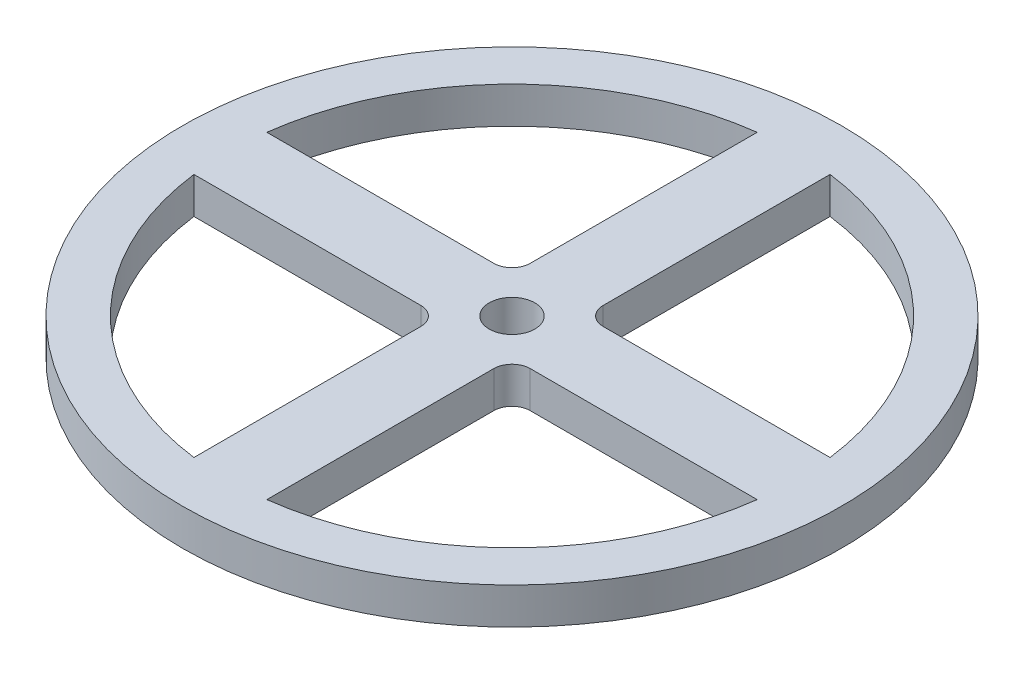
SolidWorks part; units mm, degrees
ref_plane "Front Plane" through (0, 0, 0) normal (0, 0, 1) x (1, 0, 0)
ref_plane "Top Plane" through (0, 0, 0) normal (0, 1, 0) x (1, 0, 0)
ref_plane "Right Plane" through (0, 0, 0) normal (1, 0, 0) x (0, 0, -1)
sketch "Sketch1" plane through (0, 0, 0) normal (0, 1, 0) x (1, 0, 0)
  line L0 (-43.2051, 0) -> (60.4147, 0) construction
  line L1 (0, 48.3176) -> (0, -50.4298) construction
  line L2 (-30.8921, -4) -> (-6, -4)
  line L3 (-4, 30.8921) -> (-4, 6)
  line L4 (-30.8921, 4) -> (-6, 4)
  line L5 (4, 30.8921) -> (4, 6)
  line L6 (-4, -6) -> (-4, -30.8921)
  line L7 (-4, 48.3176) -> (-4, -50.4298) construction
  line L8 (4, 48.3176) -> (4, -50.4298) construction
  line L9 (-43.2051, 4) -> (60.4147, 4) construction
  line L10 (-43.2051, -4) -> (60.4147, -4) construction
  line L11 (6, 4) -> (30.8921, 4)
  line L12 (6, -4) -> (30.8921, -4)
  line L13 (4, -6) -> (4, -30.8921)
  circle A0 centre (0, 0) radius 36.15
  circle A1 centre (0, 0) radius 2.5
  arc A2 (-30.8921, -4) -> (-4, -30.8921) centre (0, 0) ccw
  arc A5 (-6, -4) -> (-4, -6) centre (-6, -6) cw
  arc A6 (-6, 4) -> (-4, 6) centre (-6, 6) ccw
  arc A7 (4, 6) -> (6, 4) centre (6, 6) ccw
  arc A9 (6, -4) -> (4, -6) centre (6, -6) ccw
  arc A10 (-4, 30.8921) -> (-30.8921, 4) centre (0, 0) ccw
  circle A11 centre (0, 0) radius 31.15 construction
  arc A12 (30.8921, 4) -> (4, 30.8921) centre (0, 0) ccw
  arc A13 (4, -30.8921) -> (30.8921, -4) centre (0, 0) ccw
  point P38 (29.9323, 9.1512)
  dimension "D1" = 72.3
  dimension "D2" = 5
  dimension "D4" = 2
  dimension "D7" = 2
  dimension "D8" = 2
  dimension "D9" = 2
  dimension "D3" = 5
  dimension "D5" = 4
  dimension "D6" = 4
extrude "Boss-Extrude1" add sketch "Sketch1" along normal blind 4 contours A0 A13 L13 A9 L12 A12 L11 A7 L5 A10 L3 A6 L4 A1 L2 A5 L6 A2
